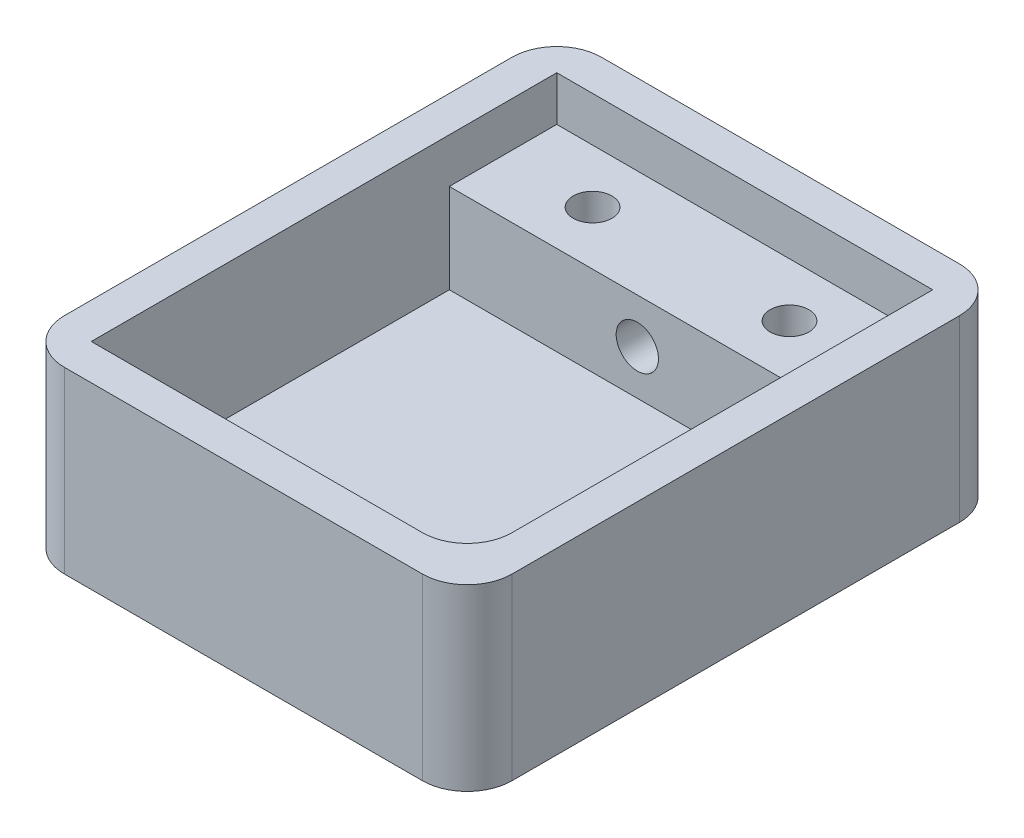
SolidWorks part; units mm, degrees
ref_plane "Front Plane" through (0, 0, 0) normal (0, 0, 1) x (1, 0, 0)
ref_plane "Top Plane" through (0, 0, 0) normal (0, 1, 0) x (1, 0, 0)
ref_plane "Right Plane" through (0, 0, 0) normal (1, 0, 0) x (0, 0, -1)
sketch "Sketch1" plane through (0, 0, 0) normal (0, 1, 0) x (1, 0, 0)
  line L1 (-15.875, -19.05) -> (15.875, -19.05)
  line L2 (-15.875, -19.05) -> (-15.875, 19.05)
  line L3 (-15.875, 19.05) -> (15.875, 19.05)
  line L4 (15.875, -19.05) -> (15.875, 19.05)
  line L5 (-15.875, -19.05) -> (15.875, 19.05) construction
  line L6 (-15.875, 19.05) -> (15.875, -19.05) construction
  point P0 (0, 0)
  dimension "D1" = 31.75
  dimension "D2" = 38.1
extrude "Boss-Extrude1" add sketch "Sketch1" along normal blind 3.175
sketch "Sketch2" plane through (0, 3.175, 0) normal (0, 1, 0) x (1, 0, 0)
  line L1 (-13.335, -16.51) -> (13.335, -16.51)
  line L2 (-13.335, -16.51) -> (-13.335, 16.51)
  line L3 (-13.335, 16.51) -> (13.335, 16.51)
  line L4 (13.335, -16.51) -> (13.335, 16.51)
  line L5 (-13.335, -16.51) -> (13.335, 16.51) construction
  line L6 (-13.335, 16.51) -> (13.335, -16.51) construction
  line L10 (15.875, -19.05) -> (15.875, 19.05)
  line L11 (15.875, 19.05) -> (-15.875, 19.05)
  line L12 (-15.875, 19.05) -> (-15.875, -19.05)
  line L13 (-15.875, -19.05) -> (15.875, -19.05)
  line L14 (15.875, -19.05) -> (15.875, 19.05)
  line L15 (15.875, 19.05) -> (-15.875, 19.05)
  line L16 (-15.875, 19.05) -> (-15.875, -19.05)
  line L17 (-15.875, -19.05) -> (15.875, -19.05)
  point P0 (0, 0)
  dimension "D2" = 2.54
  dimension "D3" = 2.54
  dimension "D1" = 0
extrude "Boss-Extrude2" add sketch "Sketch2" along normal blind 9.525
sketch "Sketch3" plane through (0, 3.175, 0) normal (0, 1, 0) x (1, 0, 0)
  line L0 (13.335, -16.51) -> (13.335, 16.51) construction
  line L1 (-13.335, 16.51) -> (13.335, 16.51)
  line L2 (-13.335, 16.51) -> (-13.335, 8.89)
  line L3 (-13.335, 8.89) -> (13.335, 8.89)
  line L4 (13.335, 16.51) -> (13.335, 8.89)
  dimension "D1" = 7.62
extrude "Boss-Extrude3" add sketch "Sketch3" along normal blind 6.35
sketch "Sketch4" plane through (0, 0, 0) normal (0, -1, 0) x (1, 0, 0)
  line L0 (0, 0) -> (0, -50000) construction
  line L1 (6.985, -12.7) -> (-6.985, -12.7) construction
  line L2 (15.875, -19.05) -> (-15.875, -19.05) construction
  circle A0 centre (-6.985, -12.7) radius 2.75
  circle A1 centre (6.985, -12.7) radius 2.75
  point P6 (0, -12.7)
  dimension "D3" = 5.5
  dimension "D1" = 13.97
  dimension "D2" = 6.35
extrude "Cut-Extrude1" cut sketch "Sketch4" against normal blind 6.35
sketch "Sketch5" plane through (0, 6.35, 0) normal (0, -1, 0) x (1, 0, 0)
  line L0 (9.735, -12.7) -> (4.235, -12.7) construction
  line L1 (-4.235, -12.7) -> (-9.735, -12.7) construction
  circle A1 centre (6.985, -12.7) radius 2.75 construction
  circle A2 centre (-6.985, -12.7) radius 2.75 construction
  circle A3 centre (6.985, -12.7) radius 1.375
  circle A4 centre (-6.985, -12.7) radius 1.375
  dimension "D1" = 2.75
extrude "Cut-Extrude2" cut sketch "Sketch5" against normal through all
sketch "Sketch6" plane through (0, 0, -8.89) normal (0, 0, 1) x (1, 0, 0)
  line L0 (0, 3.175) -> (0, 9.525) construction
  line L1 (-13.335, 3.175) -> (13.335, 3.175) construction
  line L2 (-13.335, 9.525) -> (13.335, 9.525) construction
  circle A0 centre (0, 6.35) radius 1.5
  dimension "D1" = 3
extrude "Cut-Extrude3" cut sketch "Sketch6" against normal through all
fillet "Fillet1" radius 3.175 5 edges at (15.875, 6.35, 19.05) (13.335, 7.9375, 16.51) (-15.875, 6.35, 19.05) (-15.875, 6.35, -19.05) (15.875, 6.35, -19.05)
